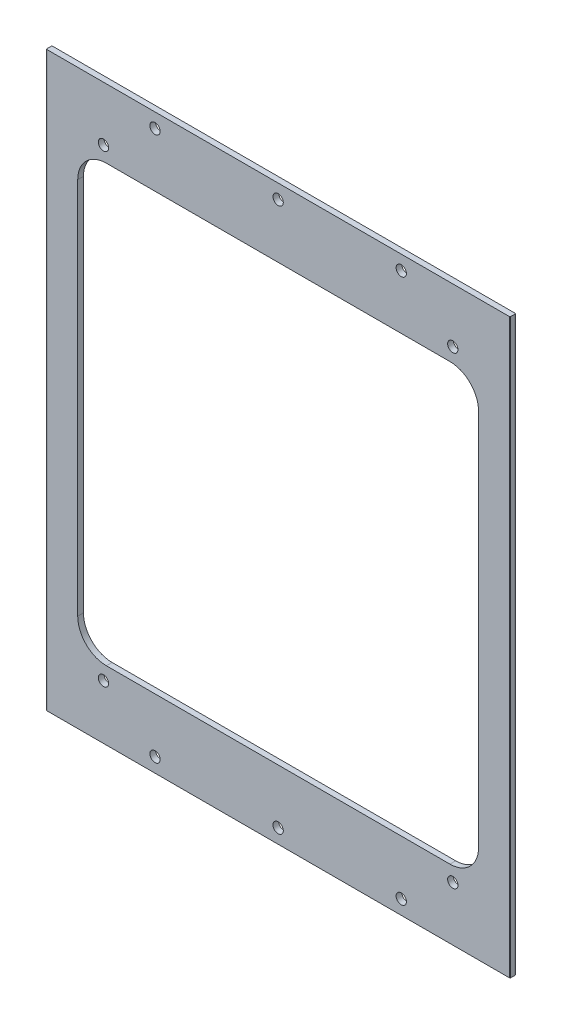
SolidWorks part; units mm, degrees
material "6061 Alloy"
ref_plane "Frontal" through (0, 0, 0) normal (0, 0, 1) x (1, 0, 0)
ref_plane "Superior" through (0, 0, 0) normal (0, 1, 0) x (1, 0, 0)
ref_plane "Direito" through (0, 0, 0) normal (1, 0, 0) x (0, 0, -1)
sketch "Sketch1" plane through (0, 0, 0) normal (0, 0, 1) x (1, 0, 0)
  line L1 (-40.5, -50) -> (40.5, -50)
  line L2 (-40.5, -50) -> (-40.5, 50)
  line L3 (-40.5, 50) -> (40.5, 50)
  line L4 (40.5, -50) -> (40.5, 50)
  line L5 (-40.5, -50) -> (40.5, 50) construction
  line L6 (-40.5, 50) -> (40.5, -50) construction
  point P0 (0, 0)
  dimension "D1" = 100
  dimension "D2" = 81
extrude "Boss-Extrude1" add sketch "Sketch1" along normal mid plane 1
sketch "Sketch2" plane through (0, 0, 0.5) normal (0, 0, 1) x (1, 0, 0)
  line L1 (-30, -38) -> (30, -38)
  line L2 (-35, -33) -> (-35, 33)
  line L3 (-30, 38) -> (30, 38)
  line L4 (35, -33) -> (35, 33)
  line L5 (-30, -33) -> (30, 33) construction
  line L6 (-30, 33) -> (30, -33) construction
  arc A0 (-35, 33) -> (-30, 38) centre (-30, 33) cw
  arc A1 (30, 38) -> (35, 33) centre (30, 33) cw
  arc A2 (35, -33) -> (30, -38) centre (30, -33) cw
  arc A3 (-30, -38) -> (-35, -33) centre (-30, -33) cw
  point P0 (0, 0)
  dimension "D1" = 5
  dimension "D2" = 5
  dimension "D3" = 5
  dimension "D4" = 5
  dimension "D5" = 70
  dimension "D6" = 76
extrude "Cut-Extrude1" cut sketch "Sketch2" against normal through all
hole_wizard "M1.6 Hole1-PCBUnion" positions "Sketch4" profile "Sketch3" hole size "M1.6" standard "DIN"
sketch "Sketch4" plane through (0, 0, 0.5) normal (0, 0, 1) x (1, 0, 0)
  line L0 (30, 38) -> (-30, 38) construction
  line L1 (-30, -38) -> (30, -38) construction
  line L2 (-40.5, 50) -> (-40.5, -50) construction
  line L3 (40.5, -50) -> (40.5, 50) construction
  point P0 (-30.5, 40.5)
  point P2 (30.5, 40.5)
  point P4 (-30.5, -40.5)
  point P6 (30.5, -40.5)
  dimension "D1" = 2.5
  dimension "D2" = 2.5
  dimension "D3" = 10
  dimension "D4" = 10
sketch "Sketch3" plane through (-30.5, 40.5, 0.5) normal (1, 0, 0) x (0, -1, 0)
  line L0 (0, 0) -> (0, 100.5408)
  line L1 (0, 100.5408) -> (0.9, 100)
  line L2 (0.9, 100) -> (0.9, 0)
  line L5 (0.9, 0) -> (0, 0)
  line L10 (0, 100.5408) -> (-0.9, 100) construction
  line L11 (0, -6.35) -> (0, 107.95) construction
  dimension "Hole Dia." = 1.8
  dimension "Hole Depth" = 100
  dimension "Drill Angle" = 118
hole_wizard "M1.6 Hole2-PlateUnion" positions "Sketch6" profile "Sketch5" hole size "M1.6" standard "DIN"
sketch "Sketch6" plane through (0, 0, 0.5) normal (0, 0, 1) x (1, 0, 0)
  line L0 (40.5, 50) -> (-40.5, 50) construction
  line L1 (-40.5, -50) -> (40.5, -50) construction
  line L2 (-40.5, 50) -> (-40.5, -50) construction
  line L3 (40.5, -50) -> (40.5, 50) construction
  point P0 (-21.5, 47.5)
  point P2 (21.5, 47.5)
  point P4 (-21.5, -47.5)
  point P6 (21.5, -47.5)
  dimension "D1" = 2.5
  dimension "D2" = 2.5
  dimension "D3" = 19
  dimension "D4" = 19
sketch "Sketch5" plane through (-21.5, 47.5, 0.5) normal (1, 0, 0) x (0, -1, 0)
  line L0 (0, 0) -> (0, 100.5408)
  line L1 (0, 100.5408) -> (0.9, 100)
  line L2 (0.9, 100) -> (0.9, 0)
  line L5 (0.9, 0) -> (0, 0)
  line L10 (0, 100.5408) -> (-0.9, 100) construction
  line L11 (0, -6.35) -> (0, 107.95) construction
  dimension "Hole Dia." = 1.8
  dimension "Hole Depth" = 100
  dimension "Drill Angle" = 118
hole_wizard "M1.6 Hole3-TopUnion" positions "Sketch8" profile "Sketch7" hole size "M1.6" standard "DIN"
sketch "Sketch8" plane through (0, 0, 0.5) normal (0, 0, 1) x (1, 0, 0)
  line L0 (-40.5, -50) -> (40.5, -50) construction
  line L1 (40.5, 50) -> (-40.5, 50) construction
  point P0 (0, 47.5)
  point P2 (0, -47.5)
  dimension "D1" = 2.5
  dimension "D2" = 2.5
sketch "Sketch7" plane through (0, 47.5, 0.5) normal (1, 0, 0) x (0, -1, 0)
  line L0 (0, 0) -> (0, 200.5408)
  line L1 (0, 200.5408) -> (0.9, 200)
  line L2 (0.9, 200) -> (0.9, 0)
  line L5 (0.9, 0) -> (0, 0)
  line L10 (0, 200.5408) -> (-0.9, 200) construction
  line L11 (0, -6.35) -> (0, 107.95) construction
  dimension "Hole Dia." = 1.8
  dimension "Hole Depth" = 200
  dimension "Drill Angle" = 118
fillet "Fillet1" radius 0.1 4 edges at (40.5, 0, -0.5) (40.5, 0, 0.5) (-40.5, 0, -0.5) (-40.5, 0, 0.5)
